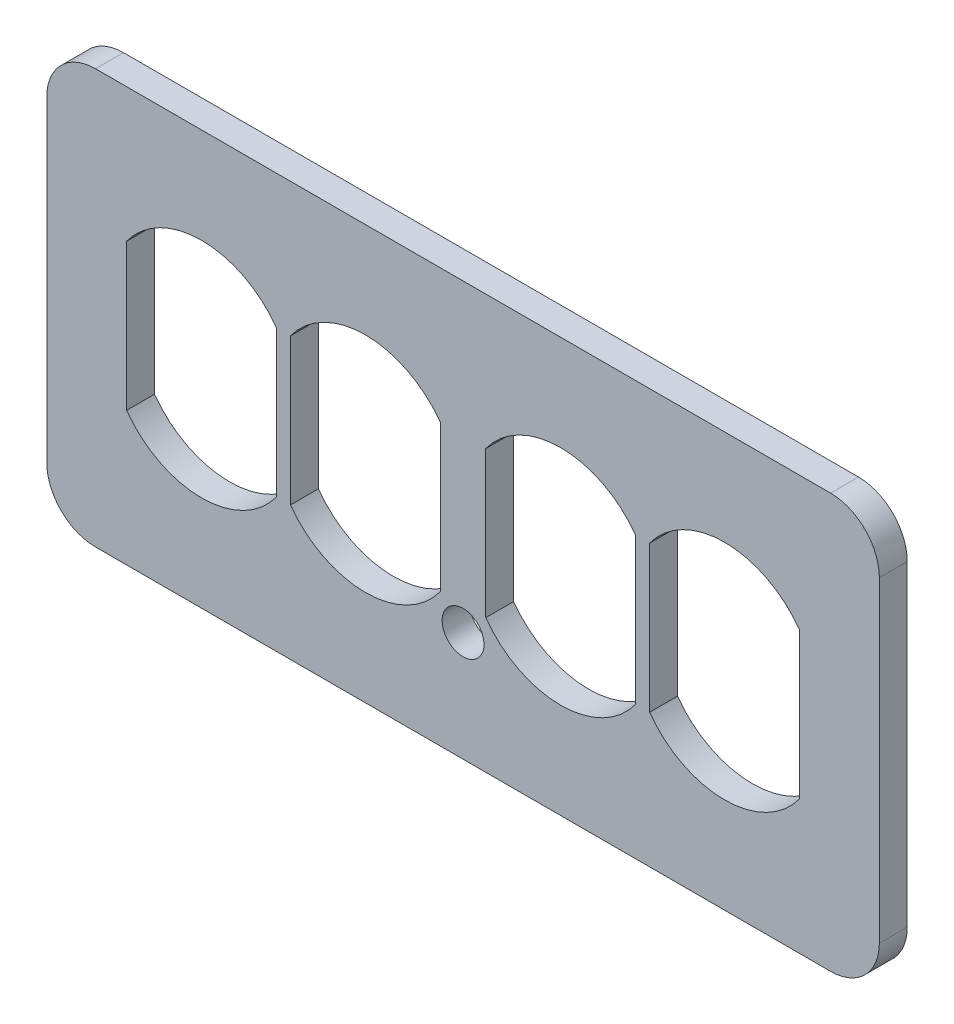
SolidWorks part; units mm, degrees
ref_plane "Спереди" through (0, 0, 0) normal (0, 0, 1) x (1, 0, 0)
ref_plane "Сверху" through (0, 0, 0) normal (0, 1, 0) x (1, 0, 0)
ref_plane "Справа" through (0, 0, 0) normal (1, 0, 0) x (0, 0, -1)
sketch "Эскиз1" plane through (0, 0, 0) normal (0, 0, 1) x (1, 0, 0)
  line L0 (0, 16.0387) -> (0, -8.9899) construction
  line L5 (-59.7, 29.7) -> (59.7, -29.7) construction
  line L6 (-59.7, -29.7) -> (59.7, 29.7) construction
  line L7 (0, 0) -> (-3.25, 0) construction
  line L8 (0, 0) -> (3.25, 0) construction
  line L9 (14, 0) -> (14, 16) construction
  line L16 (14, 0) -> (14, -16) construction
  line L27 (-3.25, -9.9722) -> (3.25, -9.9722) construction
  line L28 (0, -9.9722) -> (0, -13.9722) construction
  line L29 (3.25, 10.5) -> (3.25, -10.5)
  line L31 (24.75, 10.5) -> (24.75, -10.5)
  line L32 (3.25, 10.5) -> (24.75, -10.5) construction
  line L33 (3.25, -10.5) -> (24.75, 10.5) construction
  line L35 (48.25, 10.5) -> (48.25, -10.5)
  line L36 (26.75, 10.5) -> (26.75, -10.5)
  line L37 (-26.75, 10.5) -> (-26.75, -10.5)
  line L38 (-59.7, 29.7) -> (59.7, 29.7)
  line L39 (-59.7, 29.7) -> (-59.7, -29.7)
  line L40 (-59.7, -29.7) -> (59.7, -29.7)
  line L41 (59.7, 29.7) -> (59.7, -29.7)
  line L42 (-48.25, 10.5) -> (-48.25, -10.5)
  line L43 (-3.25, 10.5) -> (-3.25, -10.5)
  line L44 (-24.75, 10.5) -> (-24.75, -10.5)
  circle A36 centre (0, -13.9722) radius 3
  arc A37 (3.25, -10.5) -> (24.75, -10.5) centre (14, -2.7443) ccw
  arc A38 (3.25, 10.5) -> (24.75, 10.5) centre (14, 2.7443) cw
  arc A41 (26.75, -10.5) -> (48.25, -10.5) centre (37.5, -2.7443) ccw
  arc A42 (26.75, 10.5) -> (48.25, 10.5) centre (37.5, 2.7443) cw
  arc A43 (-26.75, 10.5) -> (-48.25, 10.5) centre (-37.5, 2.7443) ccw
  arc A44 (-26.75, -10.5) -> (-48.25, -10.5) centre (-37.5, -2.7443) cw
  arc A45 (-3.25, 10.5) -> (-24.75, 10.5) centre (-14, 2.7443) ccw
  arc A46 (-3.25, -10.5) -> (-24.75, -10.5) centre (-14, -2.7443) cw
  point P0 (0, 0)
  point P10 (14, 0)
  point P22 (3.25, 0)
  dimension "D7" = 16
  dimension "D8" = 21
  dimension "D11" = 6
  dimension "D9" = 2
  dimension "D1" = 119.4
  dimension "D2" = 59.4
  dimension "D3" = 3.25
  dimension "D4" = 3.25
  dimension "D5" = 16
  dimension "D6" = 21.5
  dimension "D10" = 4
extrude "Бобышка-Вытянуть1" add sketch "Эскиз1" along normal blind 4
fillet "Скругление1" radius 7 4 edges at (-59.7, -29.7, 2) (-59.7, 29.7, 2) (59.7, 29.7, 2) (59.7, -29.7, 2)
